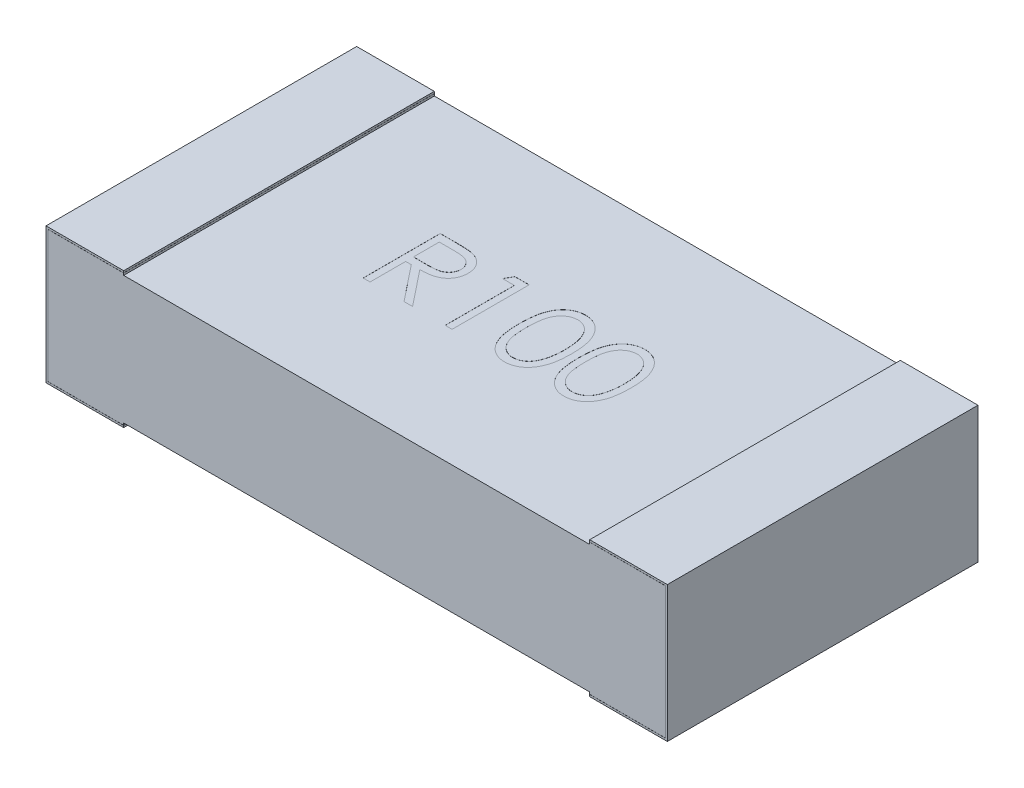
SolidWorks part; units mm, degrees
ref_plane "Front Plane" through (0, 0, 0) normal (0, 0, 1) x (1, 0, 0)
ref_plane "Top Plane" through (0, 0, 0) normal (0, 1, 0) x (1, 0, 0)
ref_plane "Right Plane" through (0, 0, 0) normal (1, 0, 0) x (0, 0, -1)
sketch "Sketch1" plane through (0, 0, 0) normal (0, 1, 0) x (1, 0, 0)
  line L1 (0, 0) -> (6.4, 0)
  line L2 (0, 0) -> (0, 3.2)
  line L3 (0, 3.2) -> (6.4, 3.2)
  line L4 (6.4, 0) -> (6.4, 3.2)
  dimension "D1" = 3.2
  dimension "D2" = 6.4
extrude "Boss-Extrude1" add sketch "Sketch1" along normal blind 1.4
sketch "Sketch2" plane through (0, 0, 0) normal (0, 0, 1) x (1, 0, 0)
  line L0 (0, 1.4) -> (0, 0) construction
  line L1 (6.4, 1.4) -> (6.4, 0) construction
  line L10 (0.8, 1.4) -> (0.8, 1.358)
  line L11 (5.6, 1.4) -> (5.6, 1.358)
  line L12 (0.8, 0.042) -> (0.8, 0)
  line L13 (5.6, 0.042) -> (5.6, 0)
  line L14 (6.358, 0.042) -> (6.358, 1.358)
  line L15 (0.042, 0.042) -> (6.358, 0.042)
  line L16 (0.042, 1.358) -> (0.042, 0.042)
  line L17 (6.358, 1.358) -> (0.042, 1.358)
  line L19 (0.8, 0.042) -> (5.6, 0.042)
  line L21 (5.6, 1.358) -> (0.8, 1.358)
  line L22 (0, 0) -> (6.4, 0)
  line L23 (6.4, 0) -> (6.4, 1.4)
  line L24 (6.4, 1.4) -> (0, 1.4)
  line L25 (0, 1.4) -> (0, 0)
  line L26 (0.8, 0) -> (5.6, 0)
  line L28 (5.6, 1.4) -> (0.8, 1.4)
  dimension "D3" = 0.8
  dimension "D4" = 0.8
  dimension "D1" = 0.042
  dimension "D2" = 0
extrude "Cut-Extrude1" cut sketch "Sketch2" against normal through all
sketch "Sketch5" plane through (0, 0, 0) normal (0, 0, 1) x (1, 0, 0)
  line L10 (0.78, 0.021) -> (0.021, 0.021)
  line L11 (0.021, 0.021) -> (0.021, 1.379)
  line L12 (0.021, 1.379) -> (0.8, 1.379)
  line L13 (0.78, 0.02) -> (0.8, 0.02)
  line L14 (0.78, 0.021) -> (0.78, 0.02)
  line L15 (0.78, 0.02) -> (0.02, 0.02)
  line L16 (0.02, 0.02) -> (0.02, 1.38)
  line L17 (0.02, 1.38) -> (0.8, 1.38)
  line L18 (5.6, 1.38) -> (5.6, 1.379)
  line L19 (0.78, 0.02) -> (0.02, 0.02)
  line L20 (0.02, 0.02) -> (0.02, 1.38)
  line L21 (0.02, 1.38) -> (0.8, 1.38)
  line L22 (0.8, 0.042) -> (0.8, 0) construction
  line L23 (0.78, 0.021) -> (0.8, 0.021)
  line L24 (0.8, 0.021) -> (0.8, 0.02)
  line L25 (3.2, 1.358) -> (3.2, 0.042) construction
  line L26 (0.8, 1.358) -> (5.6, 1.358) construction
  line L27 (5.6, 0.042) -> (0.8, 0.042) construction
  line L28 (5.6, 0.021) -> (5.6, 0.02)
  line L29 (5.62, 0.021) -> (5.6, 0.021)
  line L30 (6.38, 1.38) -> (5.6, 1.38)
  line L31 (6.38, 0.02) -> (6.38, 1.38)
  line L32 (5.62, 0.02) -> (6.38, 0.02)
  line L34 (5.62, 0.02) -> (5.6, 0.02)
  line L35 (6.379, 1.379) -> (5.6, 1.379)
  line L36 (6.379, 0.021) -> (6.379, 1.379)
  line L37 (5.62, 0.021) -> (6.379, 0.021)
  line M6 (0.8, 0) -> (0.8, 0.042)
  line M14 (0.8, 1.358) -> (0.8, 1.4)
  dimension "D1" = 0.02
  dimension "D2" = 0.001
extrude "Cut-Extrude2" cut sketch "Sketch5" against normal through all contours L23 L10 L11 L12 L21 L20 L19 L13 M14 M6 | L35 L18 L30 L31 L32 L34 L28 L29 L37 L36
sketch "Sketch6" plane through (0, 1.358, 0) normal (0, 1, 0) x (1, 0, 0)
  text T0 "R100" font "Century Gothic" height in points 3
extrude "Cut-Extrude3" cut sketch "Sketch6" against normal blind 0.001
